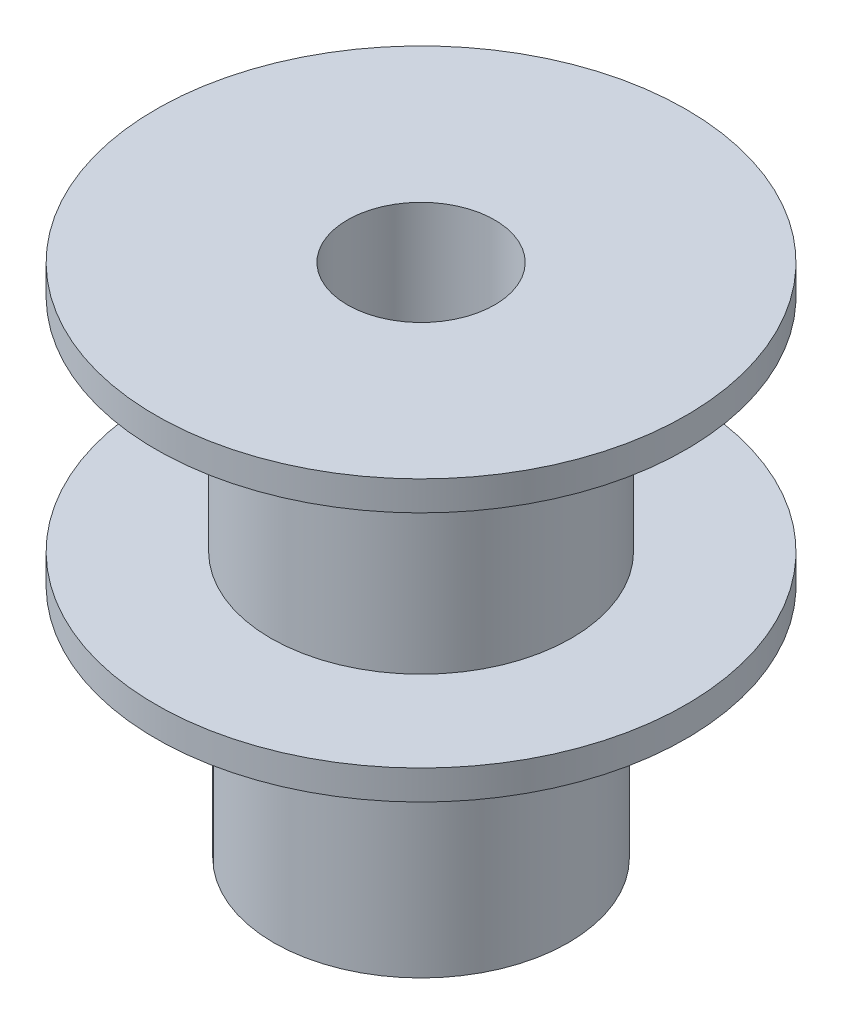
SolidWorks part; units mm, degrees
material "Chrome Stainless Steel"
ref_plane "Front Plane" through (0, 0, 0) normal (0, 0, 1) x (1, 0, 0)
ref_plane "Top Plane" through (0, 0, 0) normal (0, 1, 0) x (1, 0, 0)
ref_plane "Right Plane" through (0, 0, 0) normal (1, 0, 0) x (0, 0, -1)
sketch "Sketch1" plane through (0, 0, 0) normal (0, 0, 1) x (1, 0, 0)
  line L0 (0, 0) -> (0, 17.5)
  line L1 (0, 17.5) -> (9, 17.5)
  line L2 (9, 17.5) -> (9, 16.5)
  line L3 (9, 16.5) -> (5.1, 16.5)
  line L4 (5.1, 16.5) -> (5.1, 9)
  line L5 (5.1, 9) -> (9, 9)
  line L8 (9, 9) -> (9, 8)
  line L9 (9, 8) -> (5, 8)
  line L10 (5, 8) -> (5, 0)
  line L11 (5, 0) -> (0, 0)
  dimension "D1" = 17.5
  dimension "D2" = 9
  dimension "D3" = 7.5
  dimension "D4" = 5
  dimension "D5" = 8
  dimension "D6" = 5.1
revolve "Revolve1" add sketch "Sketch1" angle 360 about L0
sketch "Sketch3" plane through (0, 17.5, 0) normal (0, 1, 0) x (1, 0, 0)
  circle A0 centre (0, 0) radius 2.5
extrude "Cut-Extrude2" cut sketch "Sketch3" against normal through all
sketch "Sketch4" plane through (0, 0, 0) normal (1, 0, 0) x (0, 0, -1)
  line L0 (0, 9.625) -> (0, -9.625) construction
  line L1 (9.9, 0) -> (-9.9, 0) construction
  circle A0 centre (0, 4) radius 1.5
  dimension "D1" = 3
  dimension "D2" = 4
extrude "Cut-Extrude3" cut sketch "Sketch4" against normal up to next
